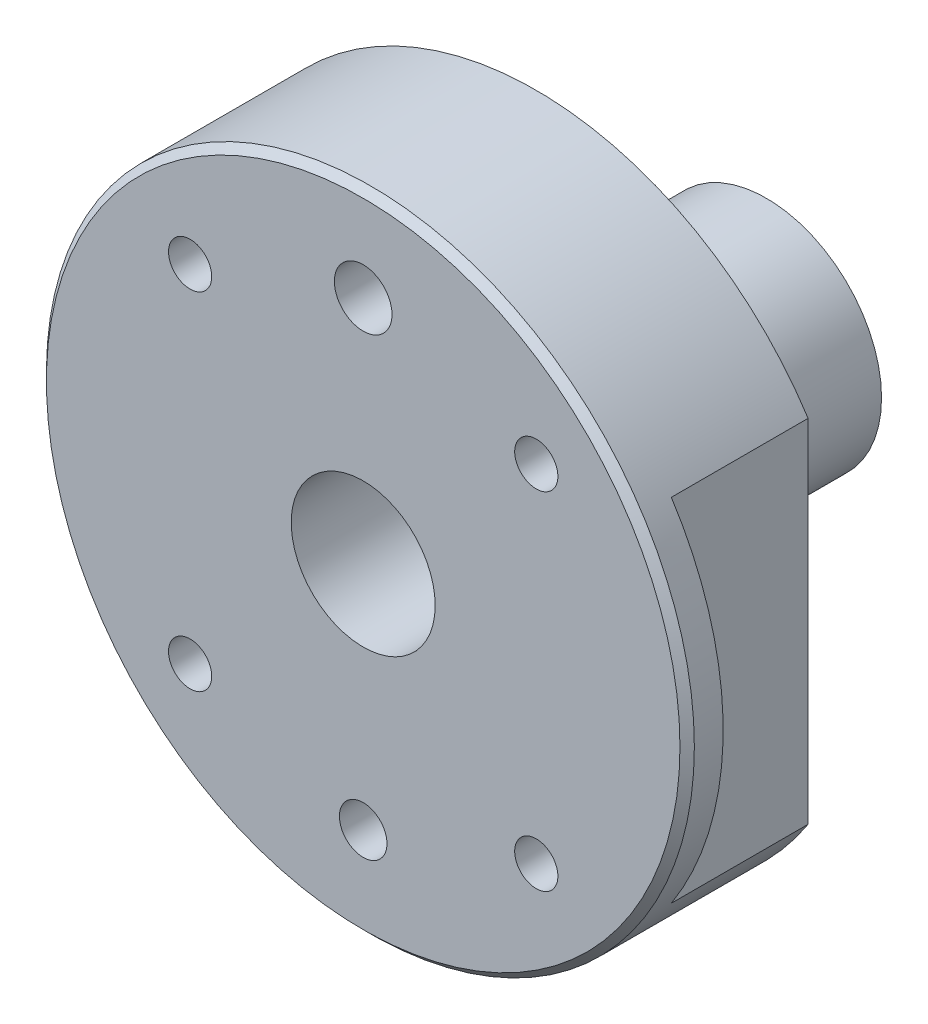
SolidWorks part; units mm, degrees
material "6061 合金"
ref_plane "前视基准面" through (0, 0, 0) normal (0, 0, 1) x (1, 0, 0)
ref_plane "上视基准面" through (0, 0, 0) normal (0, 1, 0) x (1, 0, 0)
ref_plane "右视基准面" through (0, 0, 0) normal (1, 0, 0) x (0, 0, -1)
sketch "草图1" plane through (0, 0, 0) normal (0, 0, 1) x (1, 0, 0)
  circle A0 centre (0, 0) radius 22.5
  circle A1 centre (0, 0) radius 5
  dimension "D1" = 45
  dimension "D2" = 10
extrude "凸台-拉伸1" add sketch "草图1" along normal blind 12
sketch "草图2" plane through (0, 0, 12) normal (0, 0, 1) x (1, 0, 0)
  line L0 (0, 0) -> (12.0208, 12.0208) construction
  circle A0 centre (0, 0) radius 17 construction
  circle A1 centre (12.0208, 12.0208) radius 1.5
  circle A2 centre (12.0208, -12.0208) radius 1.5
  circle A3 centre (-12.0208, -12.0208) radius 1.5
  circle A4 centre (-12.0208, 12.0208) radius 1.5
  point P11 (0, 0)
  dimension "D1" = 34
  dimension "D2" = 3
  dimension "D3" = 4
extrude "切除-拉伸1" cut sketch "草图2" against normal blind 5.5
chamfer "倒角1" distance 0.5 angle 45 1 edges at (22.5, 0, 12)
sketch "草图3" plane through (0, 0, 0) normal (0, 0, -1) x (-1, 0, 0)
  line L1 (-18.9, -25) -> (18.9, -25)
  line L2 (-18.9, -25) -> (-18.9, 25)
  line L3 (-18.9, 25) -> (18.9, 25)
  line L4 (18.9, -25) -> (18.9, 25)
  line L5 (-18.9, -25) -> (18.9, 25) construction
  line L6 (-18.9, 25) -> (18.9, -25) construction
  point P0 (0, 0)
  dimension "D1" = 37.8
  dimension "D2" = 50
extrude "切除-拉伸2" cut sketch "草图3" against normal blind 9.5 flip side to cut
sketch "草图4" plane through (0, 0, 0) normal (0, 0, -1) x (-1, 0, 0)
  circle A0 centre (0, 0) radius 4
  circle A1 centre (0, 0) radius 8
  dimension "D1" = 16
  dimension "D2" = 8
extrude "凸台-拉伸2" add sketch "草图4" along normal blind 16
sketch "草图5" plane through (0, 0, 0) normal (0, 0, -1) x (-1, 0, 0)
  line L0 (0, 22.5) -> (0, -22.5) construction
  arc A0 (18.9, 12.2082) -> (-18.9, 12.2082) centre (0, 0) ccw construction
  arc A1 (-18.9, -12.2082) -> (18.9, -12.2082) centre (0, 0) ccw construction
  circle A2 centre (0, 16) radius 2
  circle A3 centre (0, -16) radius 1.65
  dimension "D1" = 16
  dimension "D2" = 4
  dimension "D3" = 3.3
  dimension "D4" = 16
extrude "切除-拉伸3" cut sketch "草图5" against normal blind 16.5
